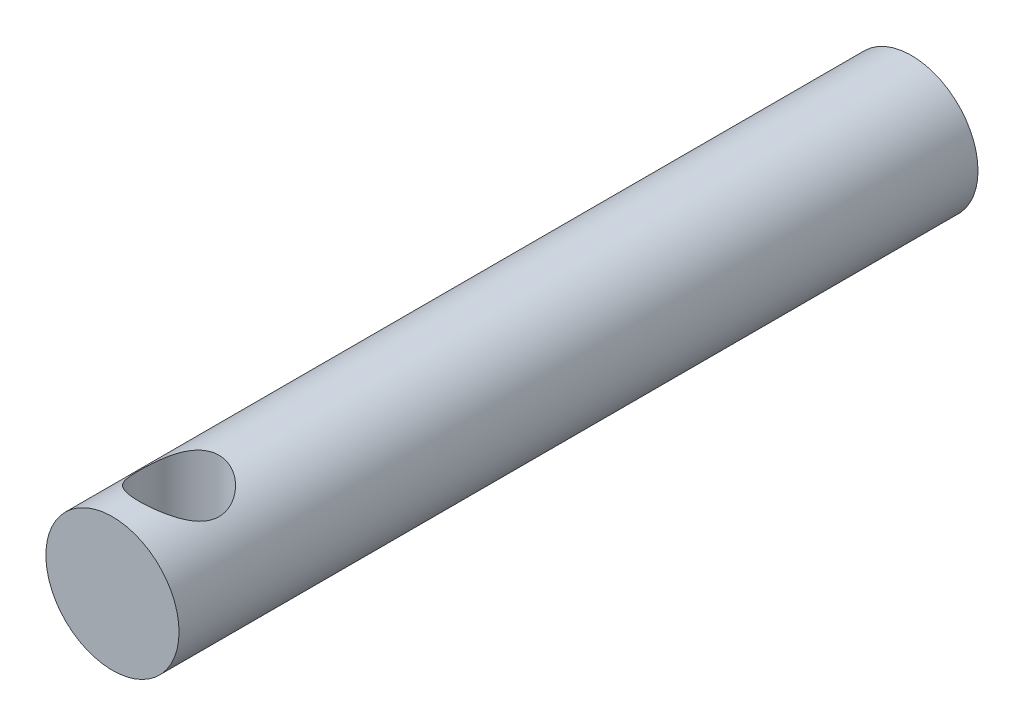
SolidWorks part; units mm, degrees
material "6061 Alloy"
ref_plane "Front Plane" through (0, 0, 0) normal (0, 0, 1) x (1, 0, 0)
ref_plane "Top Plane" through (0, 0, 0) normal (0, 1, 0) x (1, 0, 0)
ref_plane "Right Plane" through (0, 0, 0) normal (1, 0, 0) x (0, 0, -1)
sketch "Sketch1" plane through (0, 0, 0) normal (0, 0, 1) x (1, 0, 0)
  circle A0 centre (0, 0) radius 2.5
  dimension "D1" = 5
extrude "Boss-Extrude1" add sketch "Sketch1" along normal blind 30
sketch "Sketch2" plane through (0, 0, 0) normal (0, 1, 0) x (1, 0, 0)
  line L0 (-2.5, -30) -> (2.5, -30) construction
  circle A0 centre (0, -27.5) radius 1.5
  dimension "D1" = 3
  dimension "D2" = 2.5
extrude "Cut-Extrude1" cut sketch "Sketch2" against normal through all and the other way through all
